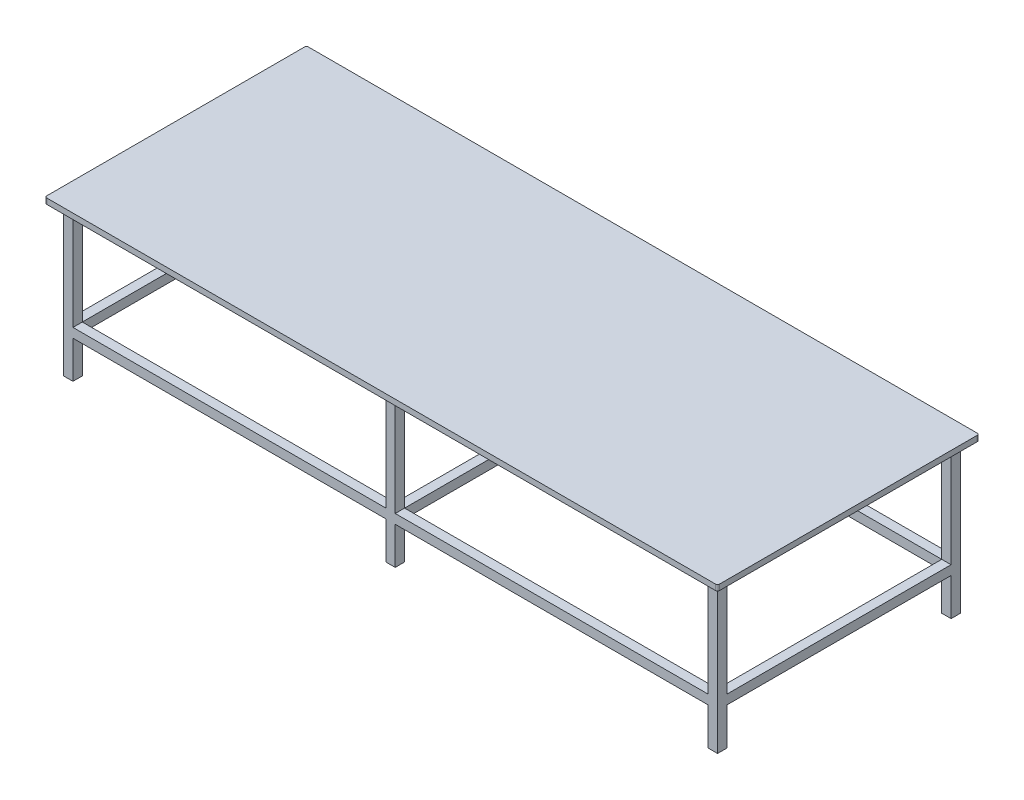
SolidWorks part; units mm, degrees
ref_plane "Ön Düzlem" through (0, 0, 0) normal (0, 0, 1) x (1, 0, 0)
ref_plane "Üst Düzlem" through (0, 0, 0) normal (0, 1, 0) x (1, 0, 0)
ref_plane "Sağ Düzlem" through (0, 0, 0) normal (1, 0, 0) x (0, 0, -1)
sketch "Çizim1" plane through (0, 0, 0) normal (0, 1, 0) x (1, 0, 0)
  line L1 (1790, -700) -> (-1790, -700)
  line L2 (1800, -690) -> (1800, 690)
  line L3 (1790, 700) -> (-1790, 700)
  line L4 (-1800, -690) -> (-1800, 690)
  line L5 (1800, -700) -> (-1800, 700) construction
  line L6 (1800, 700) -> (-1800, -700) construction
  arc A0 (-1790, -700) -> (-1800, -690) centre (-1790, -690) cw
  arc A1 (-1790, 700) -> (-1800, 690) centre (-1790, 690) ccw
  arc A2 (1800, 690) -> (1790, 700) centre (1790, 690) ccw
  arc A3 (1790, -700) -> (1800, -690) centre (1790, -690) ccw
  point P0 (0, 0)
  dimension "D1" = 10
extrude "Yükseklik-Ekstrüzyon1" add sketch "Çizim1" along normal blind 30
sketch "Çizim2" plane through (0, 0, 0) normal (0, -1, 0) x (1, 0, 0)
  line L0 (-1800, -690) -> (-1800, 690) construction
  line L1 (-1750, 650) -> (-1700, 650)
  line L2 (-1750, 650) -> (-1750, 600)
  line L3 (-1750, 600) -> (-1700, 600)
  line L4 (-1700, 650) -> (-1700, 600)
  line L5 (-1750, -650) -> (-1700, -650)
  line L6 (-1750, -650) -> (-1750, -600)
  line L7 (-1750, -600) -> (-1700, -600)
  line L8 (-1700, -650) -> (-1700, -600)
  line L9 (1750, -650) -> (1700, -650)
  line L10 (1750, -650) -> (1750, -600)
  line L11 (1750, -600) -> (1700, -600)
  line L12 (1700, -650) -> (1700, -600)
  line L13 (1750, 650) -> (1700, 650)
  line L14 (1750, 650) -> (1750, 600)
  line L15 (1750, 600) -> (1700, 600)
  line L16 (1700, 650) -> (1700, 600)
  line L17 (-1790, 700) -> (1790, 700) construction
  line L18 (1790, -700) -> (-1790, -700) construction
  line L19 (1800, 690) -> (1800, -690) construction
  line L21 (0, 650) -> (0, 600) construction
  line L22 (-25.0448, -650) -> (25.0448, -650)
  line L23 (0, -650) -> (0, -600) construction
  line L24 (-25.0448, -650) -> (-25.0448, -600)
  line L25 (-25.0448, -600) -> (25.0448, -600)
  line L26 (25.0448, -650) -> (25.0448, -600)
  line L27 (-25.0448, -650) -> (25.0448, -600) construction
  line L28 (-25.0448, -600) -> (25.0448, -650) construction
  line L29 (-25.0448, 650) -> (25.0448, 650)
  line L30 (-25.0448, 650) -> (-25.0448, 600)
  line L31 (-25.0448, 600) -> (25.0448, 600)
  line L32 (25.0448, 650) -> (25.0448, 600)
  line L33 (-25.0448, 650) -> (25.0448, 600) construction
  line L34 (-25.0448, 600) -> (25.0448, 650) construction
  point P24 (0, -625)
  point P34 (0, 625)
  dimension "D1" = 50
  dimension "D2" = 50
  dimension "D3" = 50
  dimension "D4" = 50
  dimension "D5" = 50
  dimension "D6" = 50
  dimension "D7" = 50
  dimension "D8" = 50
  dimension "D9" = 50
  dimension "D10" = 50
  dimension "D11" = 50
  dimension "D12" = 50
  dimension "D13" = 50
  dimension "D14" = 50
  dimension "D15" = 50
  dimension "D16" = 50
extrude "Yükseklik-Ekstrüzyon2" add sketch "Çizim2" along normal blind 800
ref_plane "Düzlem1" through (0, -600, 0) normal (0, -1, 0) x (-1, 0, 0)
sketch "Çizim3" plane through (0, -600, 0) normal (0, -1, 0) x (-1, 0, 0)
  line L0 (25.0448, 600) -> (1700, 600)
  line L1 (1750, -650) -> (-1750, -650)
  line L3 (1700, -600) -> (25.0448, -600)
  line L5 (-1750, 650) -> (1750, 650)
  line L7 (-1700, 600) -> (-25.0448, 600)
  line L9 (1750, 650) -> (1700, 650)
  line L10 (1750, 650) -> (1750, -650)
  line L11 (1750, -650) -> (1700, -650)
  line L12 (1700, 600) -> (1700, -600)
  line L13 (-25.0448, 650) -> (25.0448, 650)
  line L14 (-25.0448, 600) -> (-25.0448, -600)
  line L15 (-25.0448, -650) -> (25.0448, -650)
  line L16 (25.0448, 600) -> (25.0448, -650)
  line L17 (-1750, -650) -> (-1700, -650)
  line L18 (-1750, -650) -> (-1750, 650)
  line L19 (-1750, 650) -> (-1700, 650)
  line L20 (-1700, -600) -> (-1700, 600)
  line L21 (-25.0448, -600) -> (-1700, -600)
extrude "Yükseklik-Ekstrüzyon3" add sketch "Çizim3" against normal blind 50
